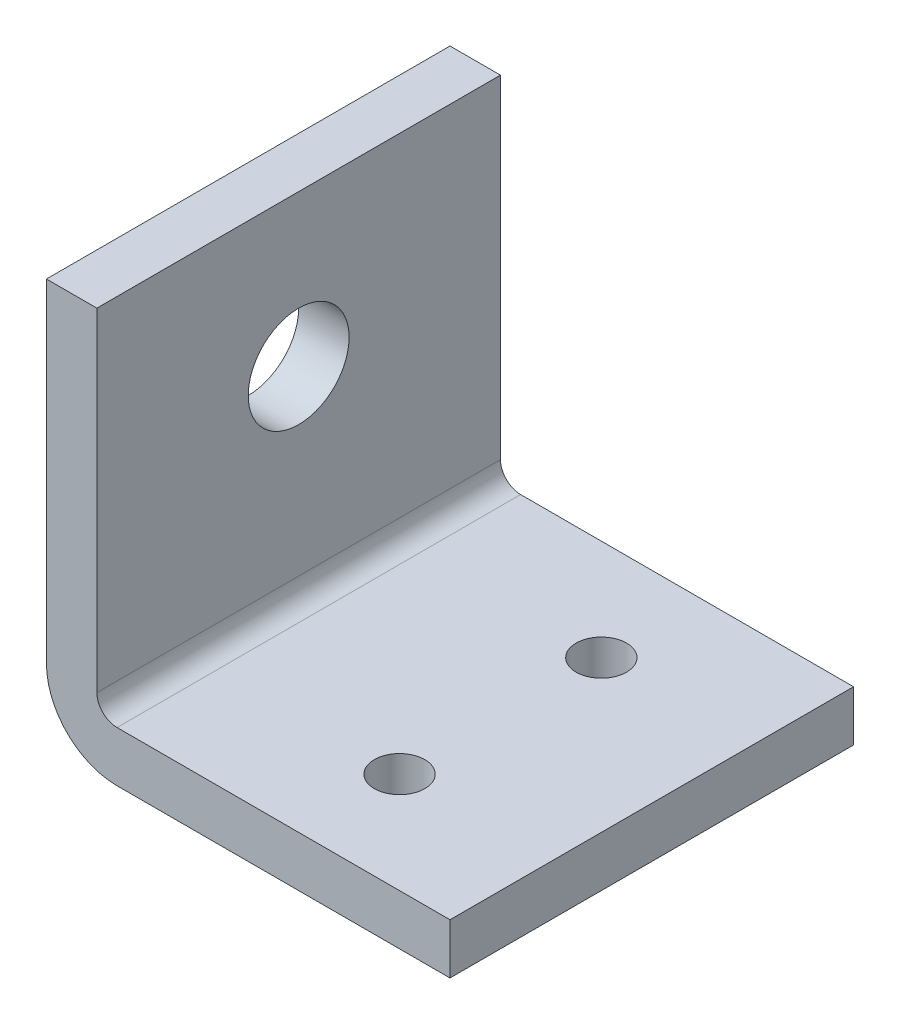
SolidWorks part; units mm, degrees
ref_plane "Front Plane" through (0, 0, 0) normal (0, 0, 1) x (1, 0, 0)
ref_plane "Top Plane" through (0, 0, 0) normal (0, 1, 0) x (1, 0, 0)
ref_plane "Right Plane" through (0, 0, 0) normal (1, 0, 0) x (0, 0, -1)
sketch "Sketch1" plane through (0, 0, 0) normal (0, 0, 1) x (1, 0, 0)
  line L1 (-20, 20) -> (20, 20)
  line L2 (-20, 20) -> (-20, -20)
  line L3 (-20, -20) -> (20, -20)
  line L4 (20, 20) -> (20, -20)
  line L5 (-20, 20) -> (20, -20) construction
  line L6 (-20, -20) -> (20, 20) construction
  point P0 (0, 0)
  dimension "D1" = 40
  dimension "D2" = 40
extrude "Boss-Extrude1" add sketch "Sketch1" along normal mid plane 40
sketch "Sketch2" plane through (0, 0, 20) normal (0, 0, 1) x (1, 0, 0)
  line L0 (20, 20) -> (-20, 20) construction
  line L1 (-15, 20) -> (20, 20)
  line L2 (-15, 20) -> (-15, -15)
  line L3 (-15, -15) -> (20, -15)
  line L4 (20, 20) -> (20, -15)
  line L5 (20, -20) -> (20, 20) construction
  line L6 (-20, -20) -> (20, -20) construction
  line L7 (-20, 20) -> (-20, -20) construction
  dimension "D1" = 5
  dimension "D2" = 5
extrude "Cut-Extrude1" cut sketch "Sketch2" against normal through all both and the other way through all
fillet "Fillet1" radius 2 1 edges at (-15, -15, 0)
fillet "Fillet2" radius 7 1 edges at (-20, -20, 0)
hole_wizard "Hole1" positions "Sketch3" profile "Sketch4" legacy end condition through all
sketch "Sketch3" plane through (-15, 0, 0) normal (1, 0, 0) x (0, 0, -1)
  line L0 (20, 20) -> (-20, 20) construction
  point P0 (0, 5)
  dimension "D1" = 15
sketch "Sketch4" plane through (-15, 5, 0) normal (0, 1, 0) x (0, 0, -1)
  line L0 (0, 0) -> (0, 5)
  line L1 (0, 5) -> (5, 5)
  line L2 (5, 5) -> (5, 0)
  line L3 (5, 0) -> (0, 0)
  line L4 (0, 110) -> (0, -10) construction
  dimension "Diameter" = 10
  dimension "Depth" = 5
hole_wizard "Hole3" positions "Sketch7" profile "Sketch8" legacy end condition through all
sketch "Sketch7" plane through (0, -15, 0) normal (0, 1, 0) x (1, 0, 0)
  line L0 (20, 20) -> (20, -20) construction
  point P0 (5, -10)
  dimension "D1" = 10
  dimension "D2" = 15
sketch "Sketch8" plane through (5, -15, 10) normal (1, 0, 0) x (0, 0, 1)
  line L0 (0, 0) -> (0, 5)
  line L1 (0, 5) -> (2.5, 5)
  line L2 (2.5, 5) -> (2.5, 0)
  line L3 (2.5, 0) -> (0, 0)
  line L4 (0, 110) -> (0, -10) construction
  dimension "Diameter" = 5
  dimension "Depth" = 5
mirror "Mirror1" about plane through (0, 0, 0) normal (0, 0, 1) of "Hole3"
